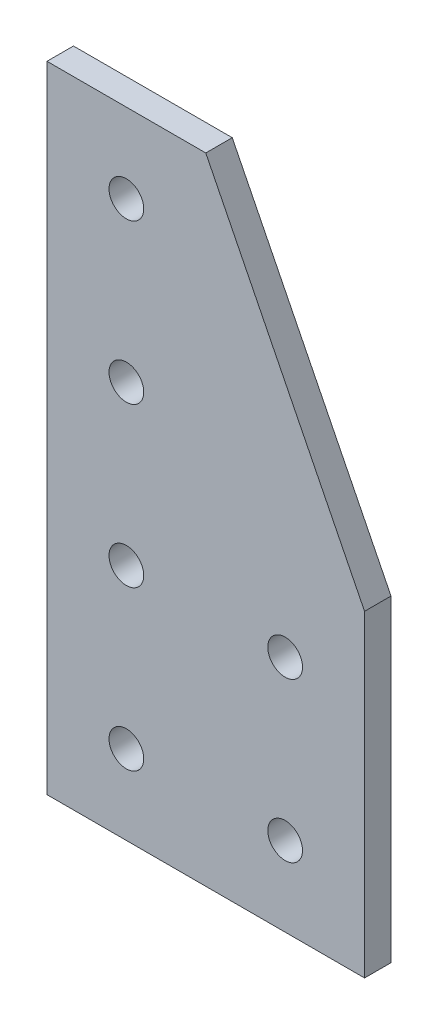
SolidWorks part; units mm, degrees
material "1060 Alloy"
ref_plane "Front Plane" through (0, 0, 0) normal (0, 0, 1) x (1, 0, 0)
ref_plane "Top Plane" through (0, 0, 0) normal (0, 1, 0) x (1, 0, 0)
ref_plane "Right Plane" through (0, 0, 0) normal (1, 0, 0) x (0, 0, -1)
sketch "Sketch1" plane through (0, 0, 0) normal (0, 0, 1) x (1, 0, 0)
  line L0 (38.1, -76.2) -> (-38.1, -76.2) construction
  line L1 (-38.1, -76.2) -> (-38.1, 76.2) construction
  line L2 (-38.1, 76.2) -> (0, 76.2) construction
  line L3 (-23.2156, -57.15) -> (-14.8844, -57.15) construction
  line L4 (0, -76.2) -> (0, -57.15) construction
  point P0 (-38.1, 0)
  point P10 (-19.05, -57.15)
  point P11 (19.05, -57.15)
sketch "Sketch2" plane through (0, 0, 0) normal (1, 0, 0) x (0, 0, -1)
  line L0 (3.175, 0) -> (-3.175, 0) construction
  point P3 (0, 0)
  dimension "Thickness" = 6.35
sketch "Sketch3" plane through (0, 0, 0) normal (0, 0, 1) x (1, 0, 0)
  line L0 (0, 76.2) -> (-38.1, 76.2)
  line L1 (-38.1, 76.2) -> (-38.1, -76.2)
  line L2 (-38.1, -76.2) -> (38.1, -76.2)
  line L3 (38.1, -76.2) -> (38.1, 0)
  line L4 (38.1, 0) -> (0, 76.2)
extrude "Boss-Extrude1" add sketch "Sketch3" along normal up to vertex (3.175 mm away) and the other way up to vertex (3.175 mm away)
sketch "Sketch4" plane through (0, 0, 3.175) normal (0, 0, 1) x (1, 0, 0)
  line L0 (-19.05, -57.15) -> (19.05, -57.15) construction
  line L1 (-19.05, -57.15) -> (-19.05, -19.05) construction
  circle A0 centre (-19.05, -57.15) radius 4.1656
  circle A1 centre (19.05, -57.15) radius 4.1656
  circle A2 centre (19.05, -19.05) radius 4.1656
  circle A3 centre (19.05, 19.05) radius 4.1656 [skipped]
  circle A4 centre (19.05, 57.15) radius 4.1656 [skipped]
  circle A5 centre (-19.05, -19.05) radius 4.1656
  circle A6 centre (-19.05, 19.05) radius 4.1656
  circle A7 centre (-19.05, 57.15) radius 4.1656
  dimension "D3" = 90
  dimension "D4" = 38.1
  dimension "D5" = 38.1
  dimension "D1" = 2
  dimension "D2" = 4
extrude "Cut-Extrude1" cut sketch "Sketch4" against normal through all
equation "\"D5@Sketch4\"=\"Hole Spacing@Sketch1\""
equation "\"D4@Sketch4\"=\"Hole Spacing@Sketch1\""
